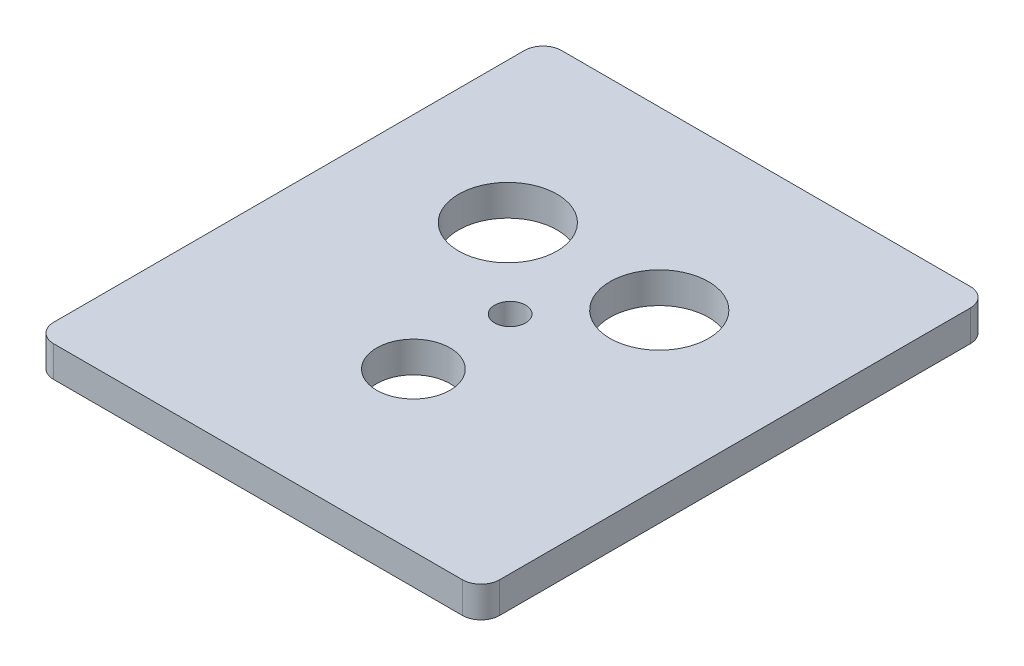
SolidWorks part; units mm, degrees
ref_plane "Front Plane" through (0, 0, 0) normal (0, 0, 1) x (1, 0, 0)
ref_plane "Top Plane" through (0, 0, 0) normal (0, 1, 0) x (1, 0, 0)
ref_plane "Right Plane" through (0, 0, 0) normal (1, 0, 0) x (0, 0, -1)
sketch "Sketch1" plane through (0, 0, 0) normal (0, 1, 0) x (1, 0, 0)
  line L1 (-34.7211, 28.3984) -> (31.2789, 28.3984)
  line L2 (-37.7211, 25.3984) -> (-37.7211, -50.6016)
  line L3 (-34.7211, -53.6016) -> (31.2789, -53.6016)
  line L4 (34.2789, 25.3984) -> (34.2789, -50.6016)
  arc A0 (-37.7211, -50.6016) -> (-34.7211, -53.6016) centre (-34.7211, -50.6016) ccw
  arc A1 (31.2789, -53.6016) -> (34.2789, -50.6016) centre (31.2789, -50.6016) ccw
  arc A2 (31.2789, 28.3984) -> (34.2789, 25.3984) centre (31.2789, 25.3984) cw
  arc A3 (-34.7211, 28.3984) -> (-37.7211, 25.3984) centre (-34.7211, 25.3984) ccw
  point P8 (34.2789, -53.6016)
  point P11 (34.2789, 28.3984)
  point P14 (-37.7211, 28.3984)
  dimension "D3" = 3
  dimension "D1" = 72
  dimension "D2" = 82
extrude "Boss-Extrude1" add sketch "Sketch1" along normal blind 5
sketch "Sketch2" plane through (0, 5, 0) normal (0, 1, 0) x (1, 0, 0)
  circle A0 centre (-14.9965, 0) radius 7.95
  circle A2 centre (9.4535, 0) radius 7.95
  dimension "D1" = 15.9
  dimension "D2" = 15.9
  dimension "D3" = 24.45
extrude "Cut-Extrude3" cut sketch "Sketch2" against normal blind 5
sketch "Sketch4" plane through (0, 5, 0) normal (0, 1, 0) x (1, 0, 0)
  circle A4 centre (-2.0246, -12.6016) radius 2.5
  circle A5 centre (-2.1394, -28.1059) radius 5.925
  dimension "D3" = 5
  dimension "D4" = 11.85
extrude "Cut-Extrude4" cut sketch "Sketch4" against normal blind 5
